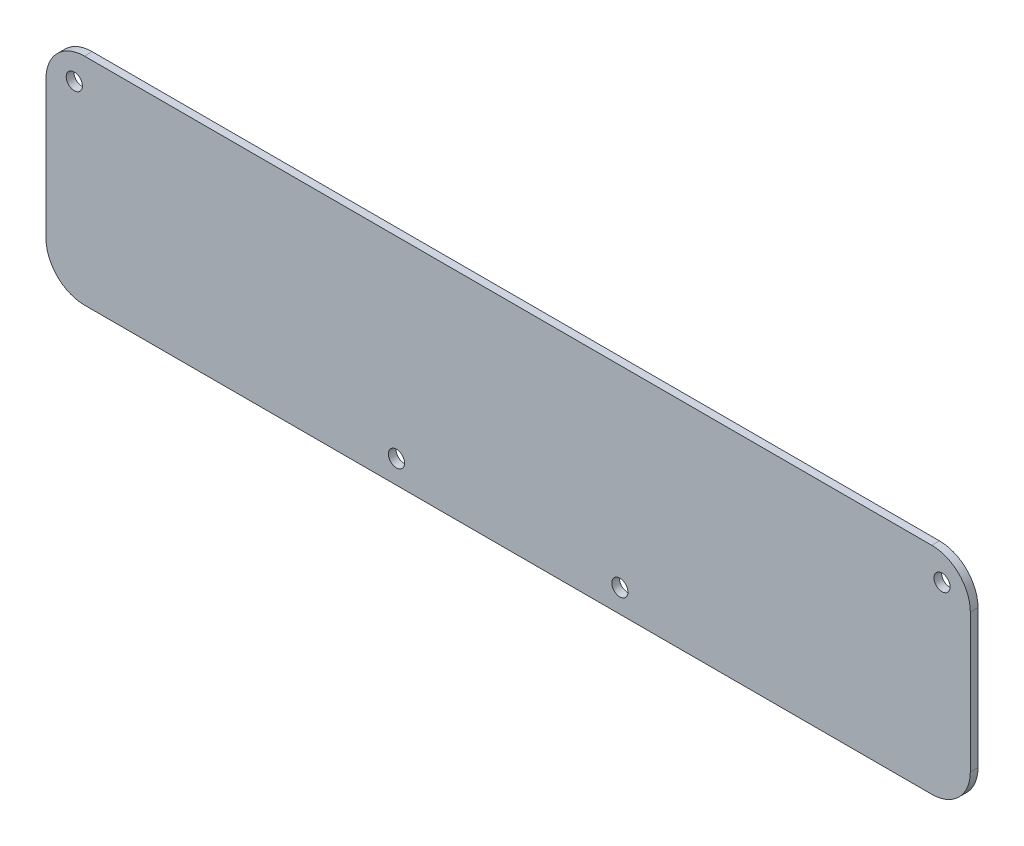
SolidWorks part; units mm, degrees
ref_plane "Front Plane" through (0, 0, 0) normal (0, 0, 1) x (1, 0, 0)
ref_plane "Top Plane" through (0, 0, 0) normal (0, 1, 0) x (1, 0, 0)
ref_plane "Right Plane" through (0, 0, 0) normal (1, 0, 0) x (0, 0, -1)
sketch "Sketch3" plane through (0, 0, 0) normal (0, 0, 1) x (1, 0, 0)
  line L0 (0, 0.0525) -> (0, 26.8296) construction
  line L1 (0, 26.8296) -> (0, -20.8296) construction
  line L2 (0, 14.0525) -> (55, 14.0525)
  line L3 (0, 14.0525) -> (-55, 14.0525)
  line L4 (0, 0.0525) -> (70.3724, 0.0525) construction
  line L5 (73.8857, 0.0525) -> (-73.8857, 0.0525) construction
  line L6 (0, -13.9475) -> (55, -13.9475)
  line L7 (0, -13.9475) -> (-55, -13.9475)
  line L8 (-60, 9.0525) -> (-60, -8.9475)
  line L9 (60, 9.0525) -> (60, -8.9475)
  circle A0 centre (-56.3279, 10.548) radius 1.05
  circle A1 centre (56.3279, 10.548) radius 1.05
  circle A2 centre (-14.5, -10.9475) radius 1.05
  circle A3 centre (14.5, -10.9475) radius 1.05
  arc A16 (55, 14.0525) -> (60, 9.0525) centre (55, 9.0525) cw
  arc A17 (55, -13.9475) -> (60, -8.9475) centre (55, -8.9475) ccw
  arc A18 (-55, -13.9475) -> (-60, -8.9475) centre (-55, -8.9475) cw
  arc A19 (-55, 14.0525) -> (-60, 9.0525) centre (-55, 9.0525) ccw
extrude "Boss-Extrude1" add sketch "Sketch3" along normal blind 1
